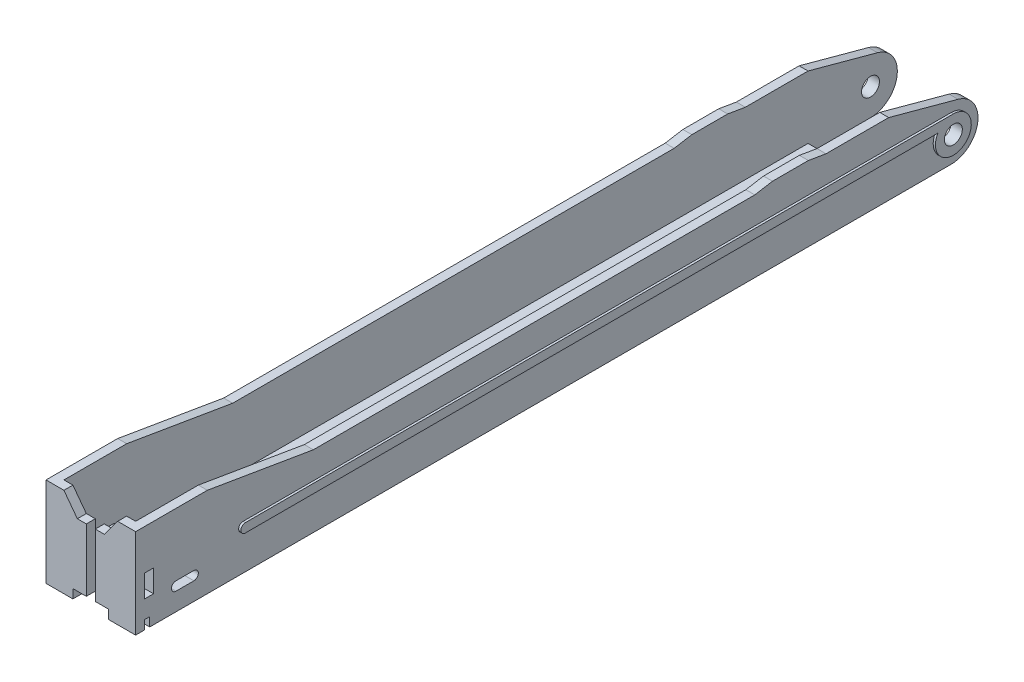
SolidWorks part; units mm, degrees
ref_plane "Front Plane" through (0, 0, 0) normal (0, 0, 1) x (1, 0, 0)
ref_plane "Top Plane" through (0, 0, 0) normal (0, 1, 0) x (1, 0, 0)
ref_plane "Right Plane" through (0, 0, 0) normal (1, 0, 0) x (0, 0, -1)
sketch "Sketch1" plane through (0, 0, 0) normal (0, 0, 1) x (1, 0, 0)
  line L1 (-7.9375, -7.9375) -> (7.9375, -7.9375)
  line L2 (-7.9375, -7.9375) -> (-7.9375, 7.9375)
  line L3 (-7.9375, 7.9375) -> (7.9375, 7.9375)
  line L4 (7.9375, -7.9375) -> (7.9375, 7.9375)
  line L5 (-7.9375, -7.9375) -> (7.9375, 7.9375) construction
  line L6 (-7.9375, 7.9375) -> (7.9375, -7.9375) construction
  point P0 (0, 0)
  dimension "D1" = 15.875
  dimension "D2" = 15.875
extrude "Boss-Extrude1" add sketch "Sketch1" against normal blind 149.225
sketch "Sketch2" plane through (7.9375, 0, 0) normal (1, 0, 0) x (0, 0, -1)
  line L0 (12.7, 7.9375) -> (31.4836, 4.7625)
  line L1 (149.225, 7.9375) -> (0, 7.9375) construction
  line L2 (149.225, -7.9375) -> (0, -7.9375) construction
  line L3 (31.4836, 4.7625) -> (109.6873, 4.7625)
  line L4 (109.6873, 4.7625) -> (112.8179, 5.2917)
  line L5 (112.8179, 5.2917) -> (119.1679, 5.2917)
  line L6 (119.1679, 5.2917) -> (122.2985, 4.7625)
  line L7 (122.2985, 4.7625) -> (133.411, 4.7625)
  line L8 (149.225, -7.9375) -> (149.225, 7.9375) construction
  line L9 (133.411, 4.7625) -> (145.7111, 1.4209)
  line L10 (144.4625, -7.9375) -> (149.225, -7.9375)
  line L11 (149.225, -7.9375) -> (149.225, 7.9375)
  line L12 (149.225, 7.9375) -> (12.7, 7.9375)
  line L13 (149.225, 7.9375) -> (12.7, 7.9375)
  arc A0 (144.4625, -7.9375) -> (145.7111, 1.4209) centre (144.4625, -3.175) ccw
  line M8 (0, -7.9375) -> (149.225, -7.9375)
  line M9 (149.225, -7.9375) -> (149.225, 7.9375)
  line M10 (149.225, 7.9375) -> (0, 7.9375)
  dimension "D10" = 9.525
  dimension "D1" = 19.05
  dimension "D2" = 12.7
  dimension "D3" = 12.7
  dimension "D4" = 78.2037
  dimension "D5" = 3.175
  dimension "D6" = 6.35
  dimension "D7" = 3.175
  dimension "D8" = 11.1125
  dimension "D9" = 13.2292
extrude "Cut-Extrude1" cut sketch "Sketch2" against normal through all both and the other way through all contours A0 L11 L0 L3 L4 L5 L6 L7 L9 M10 | A0 M8 M9
sketch "Sketch4" plane through (0, 0, 0) normal (0, 0, 1) x (1, 0, 0)
  line L0 (-6.35, 7.9375) -> (-6.35, -6.35)
  line L1 (7.9375, 7.9375) -> (-7.9375, 7.9375) construction
  line L2 (-6.35, -6.35) -> (6.35, -6.35)
  line L3 (6.35, -6.35) -> (6.35, 7.9375)
  line L4 (6.35, 7.9375) -> (-6.35, 7.9375)
  line L5 (-7.9375, 7.9375) -> (-7.9375, -7.9375) construction
  line L6 (7.9375, -7.9375) -> (7.9375, 7.9375) construction
  line L7 (-7.9375, -7.9375) -> (7.9375, -7.9375) construction
  dimension "D1" = 1.5875
  dimension "D2" = 1.5875
  dimension "D3" = 1.5875
extrude "Cut-Extrude2" cut sketch "Sketch4" against normal blind 149.225 from offset 1.5875 offset against normal yes
sketch "Sketch5" plane through (0, -7.9375, 0) normal (0, -1, 0) x (1, 0, 0)
  line L0 (0, 0) -> (0, -18.3671) construction
  line L1 (2.3812, -6.35) -> (-2.3812, -6.35)
  line L2 (-2.3812, -6.35) -> (-4.2836, -2.4977)
  line L3 (-4.2836, -2.4977) -> (-6.35, -2.4977)
  line L4 (-6.35, -2.4977) -> (-6.35, -1.5875)
  line L5 (-6.35, -1.5875) -> (-0.7937, -1.5875)
  line L6 (-7.9375, 0) -> (7.9375, 0) construction
  line L7 (-7.9375, -144.4625) -> (-7.9375, 0) construction
  line L8 (-0.7937, -1.5875) -> (-0.7937, 0)
  line L9 (-0.7937, 0) -> (0.7937, 0)
  line L10 (0.7937, -1.5875) -> (0.7937, 0)
  line L11 (2.3812, -6.35) -> (4.2836, -2.4977)
  line L12 (4.2836, -2.4977) -> (6.35, -2.4977)
  line L13 (6.35, -2.4977) -> (6.35, -1.5875)
  line L14 (6.35, -1.5875) -> (0.7937, -1.5875)
  point P17 (0, -6.35)
  dimension "D1" = 1.5875
  dimension "D2" = 1.5875
  dimension "D3" = 6.35
  dimension "D4" = 0.9102
  dimension "D5" = 2.3813
  dimension "D6" = 2.0664
  dimension "D7" = 0.7937
extrude "Cut-Extrude4" cut sketch "Sketch5" against normal through all
sketch "Sketch6" plane through (0, 0, 0) normal (0, 0, 1) x (1, 0, 0)
  line L0 (7.9375, 7.9375) -> (4.7625, 7.9375)
  line L1 (7.9375, 7.9375) -> (0.7937, 7.9375) construction
  line L2 (0.7937, 4.7625) -> (2.3812, 4.7625)
  line L3 (0.7937, 7.9375) -> (0.7937, -7.9375) construction
  line L4 (2.3812, 4.7625) -> (4.7625, 7.9375)
  line L5 (0.7937, -7.9375) -> (7.9375, -7.9375) construction
  line L6 (4.7625, 7.9375) -> (0.7937, 7.9375)
  line L7 (0.7937, 7.9375) -> (0.7937, 4.7625)
  line L8 (0, 0) -> (0, 9.6833) construction
  line L9 (-0.7937, 4.7625) -> (-2.3812, 4.7625)
  line L10 (-2.3812, 4.7625) -> (-4.7625, 7.9375)
  line L11 (-4.7625, 7.9375) -> (-0.7937, 7.9375)
  line L12 (-0.7937, 7.9375) -> (-0.7937, 4.7625)
  line L13 (0, 0) -> (0, -9.7472) construction
  line L14 (-3.175, -6.35) -> (3.175, -6.35)
  line L15 (3.175, -6.35) -> (3.175, -7.9375)
  line L16 (3.175, -7.9375) -> (-3.175, -7.9375)
  line L17 (-2.3812, -7.9375) -> (2.3812, -7.9375) construction
  line L18 (0, -7.9375) -> (0, -6.35)
  line L19 (-3.175, -6.35) -> (-3.175, -7.9375)
  dimension "D1" = 3.175
  dimension "D2" = 1.5875
  dimension "D3" = 12.7
  dimension "D4" = 3.175
  dimension "D5" = 1.5875
extrude "Cut-Extrude5" cut sketch "Sketch6" against normal up to surface (1.5875 mm away) contours L9 L10 L11 L12 | L6 L7 L2 L4 | L16 L19 L14 L15 up to face at (-3.5719, 0, -1.5875)
sketch "Sketch7" plane through (0, -7.9375, 0) normal (0, -1, 0) x (1, 0, 0)
  line L0 (6.35, -1.5875) -> (7.9375, -1.5875)
  line L1 (7.9375, -144.4625) -> (7.9375, 0) construction
  line L2 (6.35, -2.4977) -> (7.9375, -2.4977)
  line L3 (7.9375, -2.4977) -> (7.9375, -1.5875)
  line L4 (6.35, -2.4977) -> (6.35, -1.5875)
  line L5 (0, 0) -> (0, -8.2316) construction
  line L6 (-6.35, -2.4977) -> (-7.9375, -2.4977)
  line L7 (-7.9375, -2.4977) -> (-7.9375, -1.5875)
  line L8 (-6.35, -1.5875) -> (-7.9375, -1.5875)
  line L9 (-6.35, -2.4977) -> (-6.35, -1.5875)
  line M14 (7.9375, -144.4625) -> (7.9375, 0)
  line M18 (6.35, -1.5875) -> (6.35, -2.4977)
extrude "Cut-Extrude6" cut sketch "Sketch7" against normal blind 1.5875 contours L2 L0 M18 M14 | L6 L7 L8 L9
sketch "Sketch8" plane through (7.9375, 0, 0) normal (1, 0, 0) x (0, 0, -1)
  line L0 (0, -7.9375) -> (0, 7.9375) construction
  line L1 (1.5875, 0.7938) -> (3.175, 0.7938)
  line L2 (1.5875, 0.7938) -> (1.5875, -3.175)
  line L3 (1.5875, -3.175) -> (3.175, -3.175)
  line L4 (3.175, 0.7938) -> (3.175, -3.175)
  line L6 (144.4625, -7.9375) -> (2.4977, -7.9375) construction
  line L7 (7.1437, -3.9688) -> (10.3187, -3.9688) construction
  line L8 (7.1437, -3.175) -> (10.3187, -3.175)
  line L9 (7.1437, -4.7625) -> (10.3187, -4.7625)
  line L10 (6.35, -3.9688) -> (0, -3.9688)
  arc A0 (7.1437, -3.175) -> (7.1437, -4.7625) centre (7.1437, -3.9688) ccw
  arc A1 (10.3187, -4.7625) -> (10.3187, -3.175) centre (10.3187, -3.9688) ccw
  circle A2 centre (144.4625, -3.175) radius 1.5875
  point P8 (8.7312, -3.9688)
  dimension "D5" = 1.5875
  dimension "D9" = 3.175
  dimension "D1" = 1.5875
  dimension "D2" = 4.7625
  dimension "D3" = 3.9688
  dimension "D4" = 1.5875
  dimension "D6" = 3.175
  dimension "D7" = 3.175
  dimension "D8" = 6.35
extrude "Cut-Extrude7" cut sketch "Sketch8" against normal through all
sketch "Sketch9" plane through (0, -7.9375, 0) normal (0, -1, 0) x (1, 0, 0)
  line L0 (0, 0) -> (0, -25.4) construction
  line L1 (0, -25.4) -> (0, -122.2375) construction
  circle A0 centre (0, -22.225) radius 3.175
  circle A1 centre (0, -122.2375) radius 3.175
  dimension "D2" = 6.35
  dimension "D4" = 6.35
  dimension "D1" = 25.4
  dimension "D3" = 96.8375
extrude "Cut-Extrude8" cut sketch "Sketch9" against normal through all contours A0 | A1
sketch "Sketch10" plane through (7.9375, 0, 0) normal (1, 0, 0) x (0, 0, -1)
  line L0 (144.4625, -3.175) -> (153.233, -3.175) construction
  line L1 (144.4625, 0) -> (19.05, 0)
  line L3 (19.05, -1.5875) -> (141.7129, -1.5875)
  line L5 (0, -7.9375) -> (0, 7.9375) construction
  arc A0 (141.7129, -1.5875) -> (144.4625, 0) centre (144.4625, -3.175) ccw
  circle A1 centre (144.4625, -3.175) radius 1.5875
  arc A2 (19.05, -1.5875) -> (19.05, 0) centre (19.05, -0.7937) cw
  dimension "D1" = 6.35
  dimension "D3" = 3.175
  dimension "D4" = 19.05
  dimension "D2" = 1.5875
extrude "Boss-Extrude2" add sketch "Sketch10" along normal blind 0.3969
mirror "Mirror1" about plane through (0, 0, 0) normal (1, 0, 0) of "Boss-Extrude2"
sketch "Sketch11" plane through (0, -6.35, 0) normal (0, 1, 0) x (1, 0, 0)
  line L0 (-6.35, 148.0123) -> (-6.35, 2.4977) construction
  line L1 (6.35, 148.0123) -> (-6.35, 148.0123)
  line L2 (6.35, 148.0123) -> (6.35, 133.411)
  line L3 (6.35, 133.411) -> (-6.35, 133.411)
  line L4 (-6.35, 148.0123) -> (-6.35, 133.411)
  line L5 (-6.35, 133.411) -> (-6.35, 145.7111) construction
  point P6 (-4.2411, 137.7228)
  point P8 (0, 0)
  point P10 (-4.9815, 139.3888)
  point P13 (0, 0)
extrude "Cut-Extrude9" cut sketch "Sketch11" against normal blind 2.54
